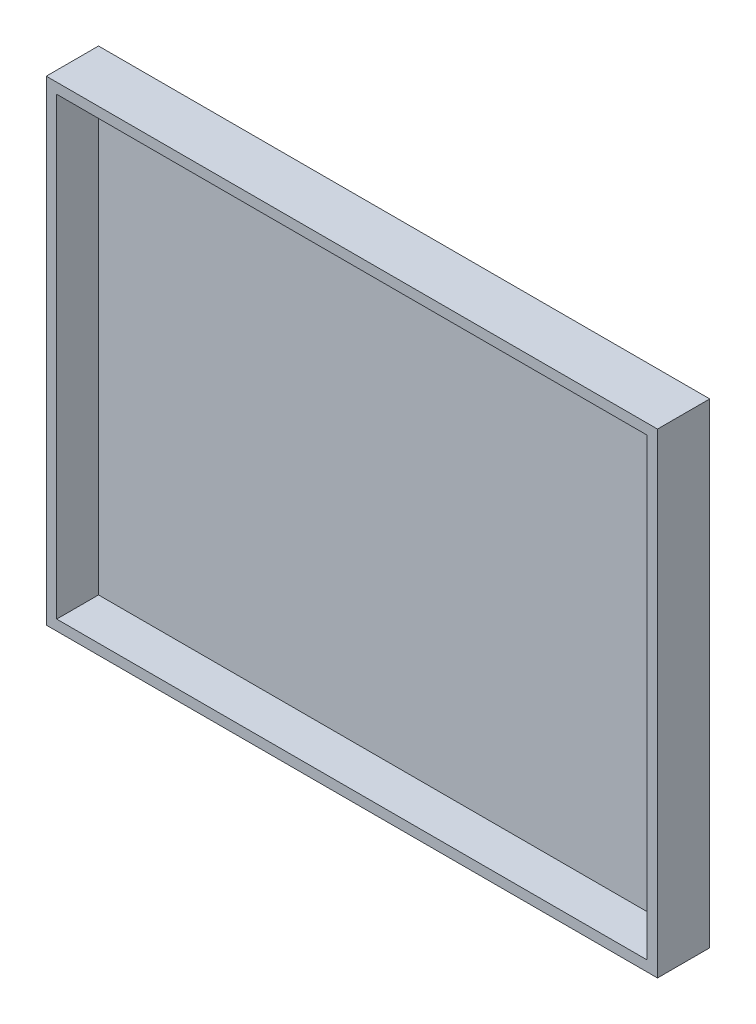
SolidWorks part; units mm, degrees
ref_plane "Plan de face" through (0, 0, 0) normal (0, 0, 1) x (1, 0, 0)
ref_plane "Plan de dessus" through (0, 0, 0) normal (0, 1, 0) x (1, 0, 0)
ref_plane "Plan de droite" through (0, 0, 0) normal (1, 0, 0) x (0, 0, -1)
sketch "Esquisse1" plane through (0, 0, 0) normal (0, 0, 1) x (1, 0, 0)
  line L1 (0, 0) -> (117, 0)
  line L2 (0, 0) -> (0, 91)
  line L3 (0, 91) -> (117, 91)
  line L4 (117, 0) -> (117, 91)
  dimension "D1" = 117
  dimension "D2" = 91
extrude "Boss.-Extru.1" add sketch "Esquisse1" along normal blind 10
sketch "Esquisse4" plane through (0, 0, 10) normal (0, 0, 1) x (1, 0, 0)
  line L0 (0, 91) -> (0, 0) construction
  line L1 (2, 89) -> (115, 89)
  line L2 (2, 89) -> (2, 2)
  line L3 (2, 2) -> (115, 2)
  line L4 (115, 89) -> (115, 2)
  line L5 (117, 91) -> (0, 91) construction
  line L6 (117, 0) -> (117, 91) construction
  line L7 (0, 0) -> (117, 0) construction
  dimension "D1" = 2
  dimension "D2" = 2
  dimension "D3" = 2
  dimension "D4" = 2
  dimension "D5" = 113
  dimension "D6" = 87
extrude "Enlèv. mat.-Extru.1" cut sketch "Esquisse4" against normal blind 8
